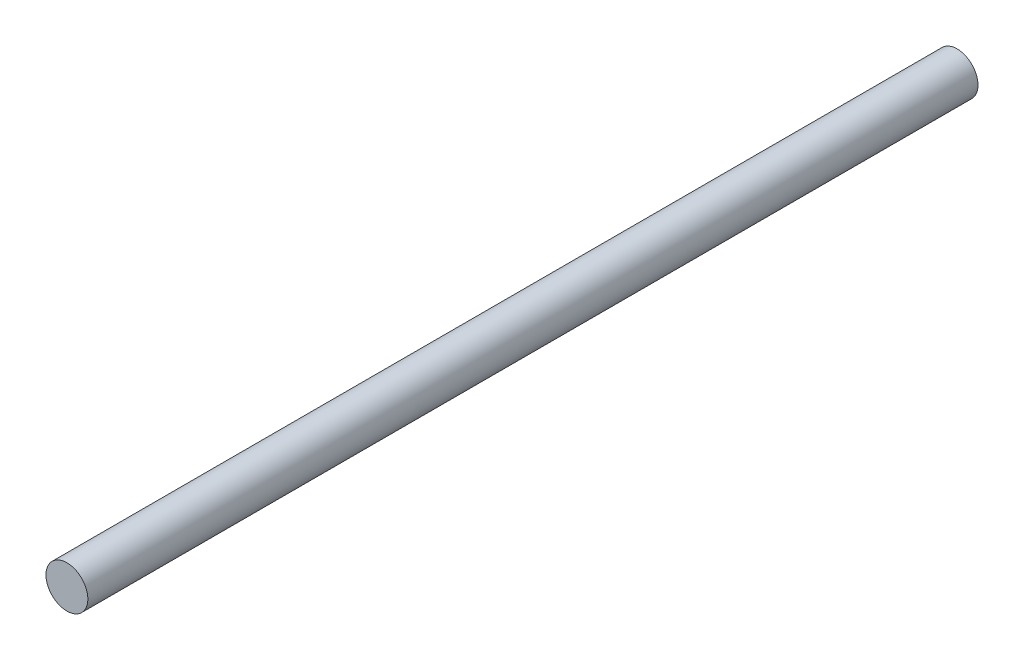
SolidWorks part; units mm, degrees
ref_plane "前视基准面" through (0, 0, 0) normal (0, 0, 1) x (1, 0, 0)
ref_plane "上视基准面" through (0, 0, 0) normal (0, 1, 0) x (1, 0, 0)
ref_plane "右视基准面" through (0, 0, 0) normal (1, 0, 0) x (0, 0, -1)
sketch "草图1" plane through (0, 0, 0) normal (0, 0, 1) x (1, 0, 0)
  circle A0 centre (0, 0) radius 2
extrude "凸台-拉伸1" add sketch "草图1" along normal blind 85
thread "螺纹线1" [suppressed] pitch 1.27 start angle 0, offset 0, length 0, pitch 1.27, diameter 4
ref_plane "基准面1" through (-2, 0, 85) normal (0, -1, 0) x (-1, 0, 0)
sketch "螺纹线轮廓1" plane through (-2, 0, 85) normal (0, -1, 0) x (-1, 0, 0)
  line L0 (0, 0) -> (0, 1.27) construction
  line L11 (0, 0) -> (0, 1.1112)
  line L12 (0, 1.1112) -> (-0.6874, 0.7144)
  line L13 (-0.6874, 0.7144) -> (-0.6874, 0.3969)
  line L15 (-0.6874, 0.3969) -> (0, 0)
  line L17 (-0.6874, 0.5556) -> (0, 0.5556) construction
  point P2 (0, 0)
  dimension "Pitch" = 1.27
  dimension "Profile_Angle" = 60
  dimension "Profile_Land" = 0.3175
  dimension "Profile_Height" = 0.6874
